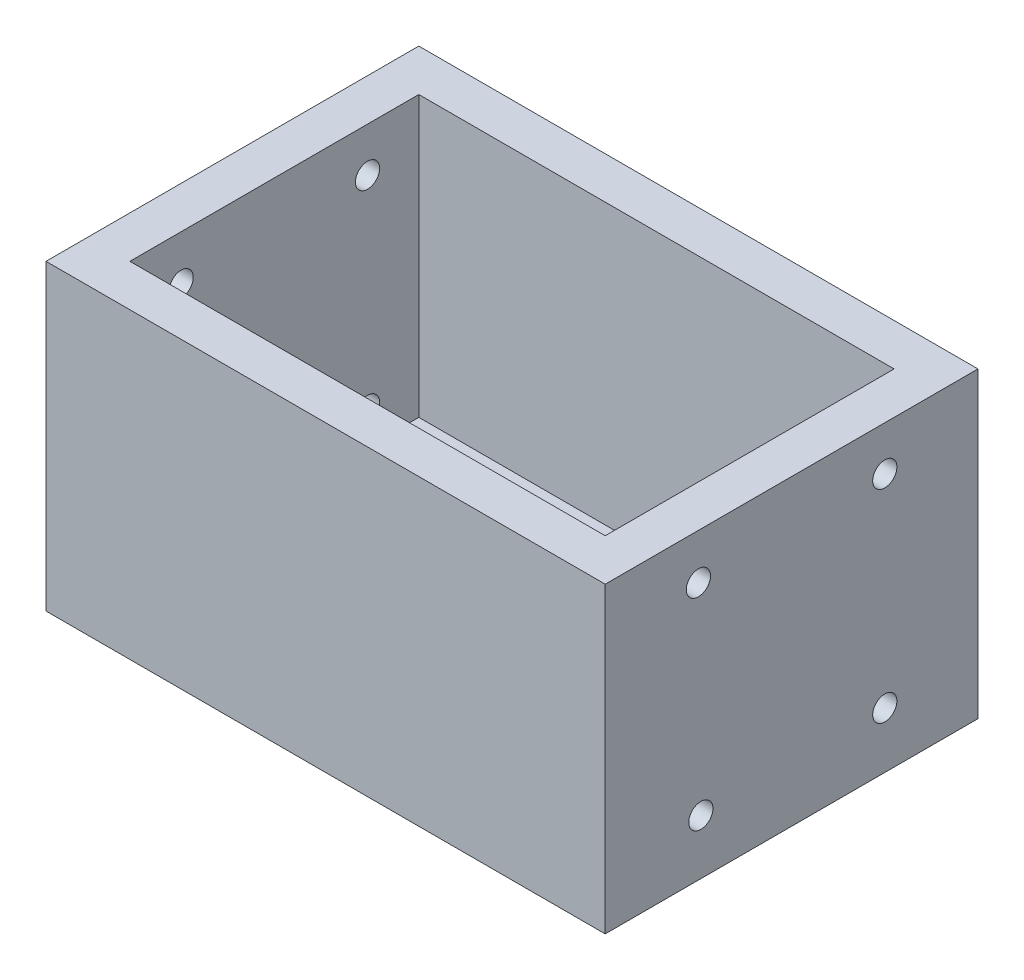
SolidWorks part; units mm, degrees
ref_plane "Front Plane" through (0, 0, 0) normal (0, 0, 1) x (1, 0, 0)
ref_plane "Top Plane" through (0, 0, 0) normal (0, 1, 0) x (1, 0, 0)
ref_plane "Right Plane" through (0, 0, 0) normal (1, 0, 0) x (0, 0, -1)
sketch "Sketch1" plane through (0, 0, 0) normal (0, 1, 0) x (1, 0, 0)
  line L1 (-51, 31) -> (51, 31)
  line L2 (-51, 31) -> (-51, -31)
  line L3 (-51, -31) -> (51, -31)
  line L4 (51, 31) -> (51, -31)
  line L5 (-51, 31) -> (51, -31) construction
  line L6 (-51, -31) -> (51, 31) construction
  line L7 (-60, 40) -> (60, 40)
  line L8 (-60, 40) -> (-60, -40)
  line L9 (-60, -40) -> (60, -40)
  line L10 (60, 40) -> (60, -40)
  line L11 (-60, 40) -> (60, -40) construction
  line L12 (-60, -40) -> (60, 40) construction
  point P0 (0, 0)
  point P6 (0, 0)
  dimension "D1" = 62
  dimension "D2" = 102
  dimension "D3" = 80
  dimension "D4" = 120
extrude "Boss-Extrude1" add sketch "Sketch1" along normal blind 60
sketch "Sketch2" plane through (0, 0, 0) normal (0, -1, 0) x (1, 0, 0)
  line L1 (-60, 40) -> (60, 40)
  line L2 (-60, 40) -> (-60, -40)
  line L3 (-60, -40) -> (60, -40)
  line L4 (60, 40) -> (60, -40)
extrude "Boss-Extrude2" add sketch "Sketch2" along normal blind 5
sketch "Sketch5" plane through (-60, 0, 0) normal (-1, 0, 0) x (0, 0, 1)
  circle A0 centre (-20, 50.5) radius 2.6
  circle A1 centre (20, 50.2569) radius 2.6
  circle A2 centre (-20, 7) radius 2.6
  circle A3 centre (19.4713, 6.7601) radius 2.6
extrude "Cut-Extrude1" cut sketch "Sketch5" against normal through all
sketch "Sketch6" plane through (0, 0, 0) normal (0, 1, 0) x (1, 0, 0)
  circle A0 centre (0, 0) radius 5
  dimension "D1" = 10
extrude "Cut-Extrude2" cut sketch "Sketch6" against normal through all
sketch "Sketch7" plane through (0, -5, 0) normal (0, -1, 0) x (1, 0, 0)
  line L1 (-13.2654, -10) -> (13.2654, -10)
  line L2 (-13.2654, -10) -> (-13.2654, -20)
  line L3 (-13.2654, -20) -> (13.2654, -20)
  line L4 (13.2654, -10) -> (13.2654, -20)
  line L5 (-13.2654, -10) -> (13.2654, -20) construction
  line L6 (-13.2654, -20) -> (13.2654, -10) construction
  point P0 (0, -15)
  dimension "D1" = 15
  dimension "D2" = 10
  dimension "D3" = 26.5309
extrude "Boss-Extrude3" add sketch "Sketch7" along normal blind 15
sketch "Sketch8" plane through (0, -20, 0) normal (0, -1, 0) x (1, 0, 0)
  line L0 (13.2654, -10) -> (-13.2654, -10) construction
  line L1 (-2, -3.5) -> (2, -3.5)
  line L2 (-2, -3.5) -> (-2, -16.5)
  line L3 (-2, -16.5) -> (2, -16.5)
  line L4 (2, -3.5) -> (2, -16.5)
  line L5 (-2, -3.5) -> (2, -16.5) construction
  line L6 (-2, -16.5) -> (2, -3.5) construction
  line L7 (-2, -10) -> (2, -10)
  line L8 (-2, -10) -> (-2, -16.5)
  line L9 (2, -16.5) -> (2, -10)
  line L10 (2, -16.5) -> (-2, -16.5)
  line L11 (-13.2654, -20) -> (13.2654, -20) construction
  circle A0 centre (-5, -14.5) radius 1.5
  circle A1 centre (5, -14.5) radius 1.5
  point P0 (0, -10)
  line M2 (13.2654, -10) -> (-13.2654, -10)
  dimension "D6" = 3
  dimension "D7" = 3
  dimension "D1" = 13
  dimension "D2" = 4
  dimension "D3" = 8.2654
  dimension "D4" = 5.5
  dimension "D5" = 8.2654
extrude "Cut-Extrude3" cut sketch "Sketch8" against normal blind 10 contours L4 L2 L3 M2 | A0 | A1
